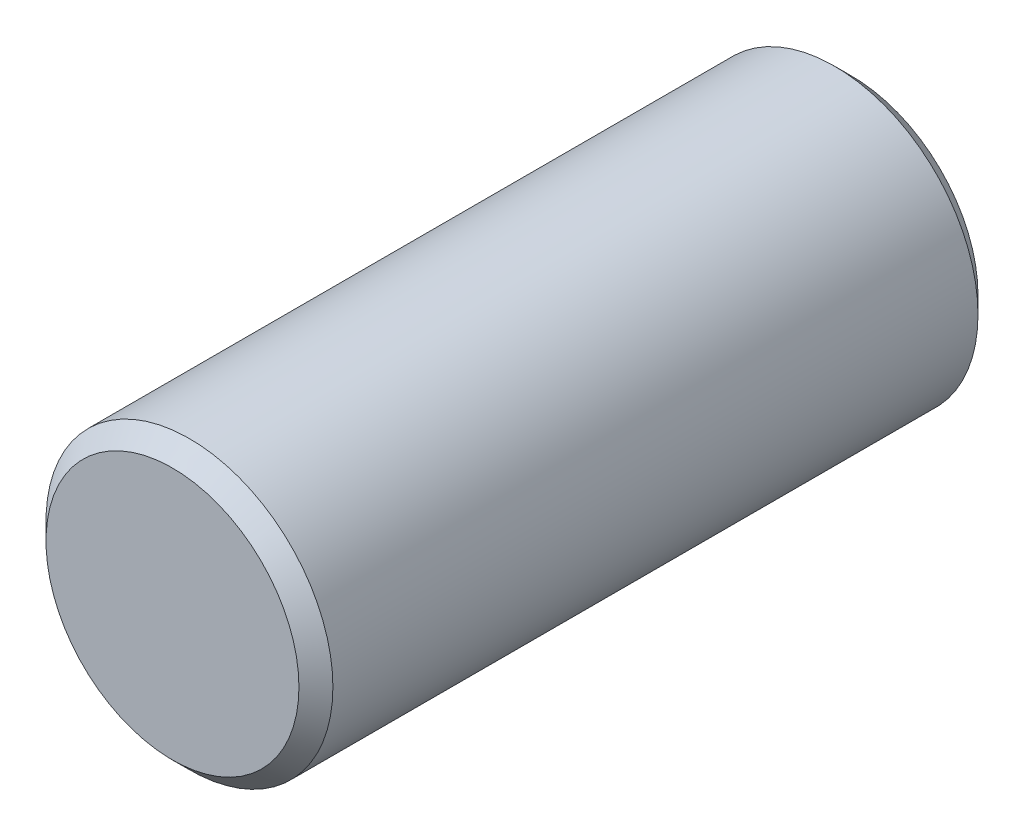
SolidWorks part; units mm, degrees
ref_plane "Front Plane" through (0, 0, 0) normal (0, 0, 1) x (1, 0, 0)
ref_plane "Top Plane" through (0, 0, 0) normal (0, 1, 0) x (1, 0, 0)
ref_plane "Right Plane" through (0, 0, 0) normal (1, 0, 0) x (0, 0, -1)
sketch "Sketch1" plane through (0, 0, 0) normal (0, 0, 1) x (1, 0, 0)
  circle A0 centre (0, 0) radius 16.9
  dimension "D1" = 33.8
extrude "Boss-Extrude1" add sketch "Sketch1" along normal blind 80
chamfer "Chamfer1" distance 2 angle 45 2 edges at (16.9, 0, 0) (16.9, 0, 80)
